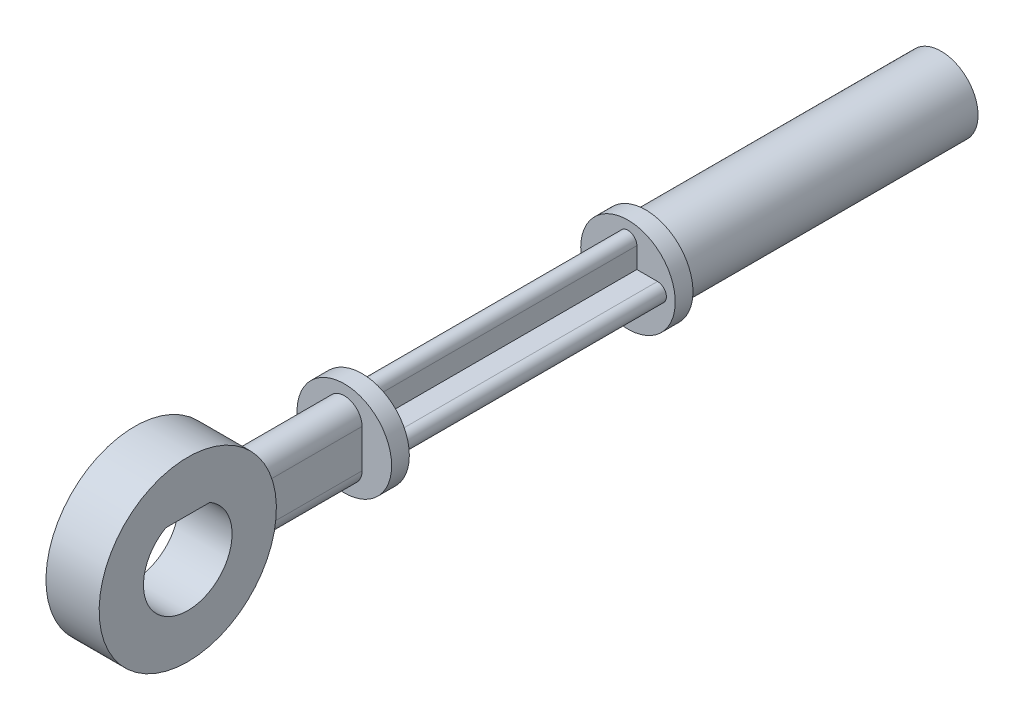
SolidWorks part; units mm, degrees
ref_plane "Front" through (0, 0, 0) normal (0, 0, 1) x (1, 0, 0)
ref_plane "Top" through (0, 0, 0) normal (0, 1, 0) x (1, 0, 0)
ref_plane "Right" through (0, 0, 0) normal (1, 0, 0) x (0, 0, -1)
sketch "Sketch1" plane through (0, 0, 0) normal (0, 0, 1) x (1, 0, 0)
  circle A0 centre (0, 0) radius 16
  dimension "D1" = 32
extrude "Base-Extrude" add sketch "Sketch1" along normal mid plane 6
sketch "Sketch2" plane through (0, 0, 3) normal (0, 0, 1) x (1, 0, 0)
  line L0 (0, 6.5) -> (0, -6.5) construction
  line L1 (6, 6.5) -> (6, -6.5)
  line L2 (-6, 6.5) -> (-6, -6.5)
  arc A0 (6, 6.5) -> (-6, 6.5) centre (0, 6.5) ccw
  arc A1 (-6, -6.5) -> (6, -6.5) centre (0, -6.5) ccw
  point P2 (0, 0)
  dimension "D1" = 12
  dimension "D2" = 25
ref_plane "Plane1" through (0, 0, 65) normal (0, 0, 1) x (1, 0, 0)
extrude "Extrude3" add sketch "Sketch2" along normal up to surface (62 mm away) up to plane "Plane1"
sketch "Sketch5" plane through (0, 0, -3) normal (0, 0, -1) x (-1, 0, 0)
  line L0 (-3, 3) -> (-3, 10)
  line L1 (3, 10) -> (3, 3)
  line L2 (3, 3) -> (10, 3)
  line L3 (10, -3) -> (3, -3)
  line L4 (3, -3) -> (3, -10)
  line L5 (-3, -10) -> (-3, -3)
  line L6 (-3, -3) -> (-10, -3)
  line L7 (-10, 3) -> (-3, 3)
  line L8 (-10, 0) -> (10, 0) construction
  line L9 (0, 10) -> (0, -10) construction
  arc A0 (-3, 10) -> (3, 10) centre (0, 10) cw
  arc A1 (10, 3) -> (10, -3) centre (10, 0) cw
  arc A2 (3, -10) -> (-3, -10) centre (0, -10) cw
  arc A3 (-10, -3) -> (-10, 3) centre (-10, 0) cw
  dimension "D1" = 26
  dimension "D3" = 26
  dimension "D2" = 6
extrude "Boss-Extrude1" add sketch "Sketch5" along normal blind 90
sketch "Sketch6" plane through (0, 0, -93) normal (0, 0, -1) x (-1, 0, 0)
  circle A0 centre (0, 0) radius 16 construction
  circle A1 centre (0, 0) radius 16
extrude "Boss-Extrude2" add sketch "Sketch6" along normal blind 6
sketch "Sketch7" plane through (0, 0, -99) normal (0, 0, -1) x (-1, 0, 0)
  circle A0 centre (0, 0) radius 12.5
  point P3 (12.5, 0)
  dimension "D1" = 25
sketch "Sketch9" plane through (0, 0, 65) normal (0, 0, 1) x (1, 0, 0)
  line L1 (-9, 30) -> (9, 30)
  line L2 (9, 30) -> (9, 0)
  line L4 (9, 0) -> (-9, 0)
  line L5 (-9, 0) -> (-9, 30)
  line L6 (9, 0) -> (54.9339, 0) construction
  dimension "D1" = 60
  dimension "D2" = 18
revolve "Boss-Revolve1" add sketch "Sketch9" angle 360 about L6
sketch "Sketch10" plane through (9, 0, 0) normal (1, 0, 0) x (0, 0, -1)
  line L0 (-72.4833, 13) -> (-57.5167, 13)
  arc A0 (-72.4833, 13) -> (-57.5167, 13) centre (-65, 0) ccw
  dimension "D1" = 30
  dimension "D2" = 28
extrude "Cut-Extrude1" cut sketch "Sketch10" against normal through all
extrude "Extrude4" add sketch "Sketch7" along normal blind 100
